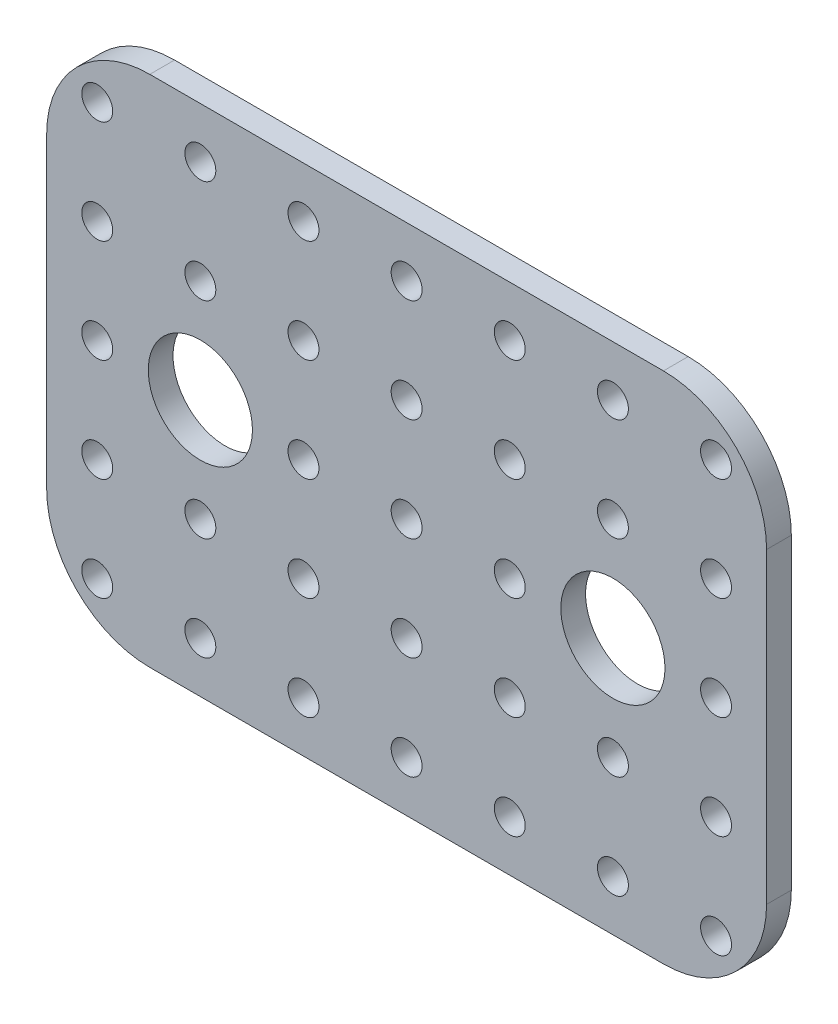
SolidWorks part; units mm, degrees
ref_plane "前视基准面" through (0, 0, 0) normal (0, 0, 1) x (1, 0, 0)
ref_plane "上视基准面" through (0, 0, 0) normal (0, 1, 0) x (1, 0, 0)
ref_plane "右视基准面" through (0, 0, 0) normal (1, 0, 0) x (0, 0, -1)
sketch "草图1" plane through (0, 0, 0) normal (0, 0, 1) x (1, 0, 0)
  line L1 (34.9, -24.9) -> (-34.9, -24.9)
  line L2 (34.9, -24.9) -> (34.9, 24.9)
  line L3 (34.9, 24.9) -> (-34.9, 24.9)
  line L4 (-34.9, -24.9) -> (-34.9, 24.9)
  line L5 (34.9, -24.9) -> (-34.9, 24.9) construction
  line L6 (34.9, 24.9) -> (-34.9, -24.9) construction
  point P0 (0, 0)
  dimension "D1" = 69.8
  dimension "D2" = 49.8
extrude "凸台-拉伸1" add sketch "草图1" along normal blind 2.4
sketch "草图2" plane through (0, 0, 2.4) normal (0, 0, 1) x (1, 0, 0)
  circle A0 centre (30, 20) radius 1.5
  circle A1 centre (20, 20) radius 1.5
  circle A2 centre (10, 20) radius 1.5
  circle A3 centre (0, 20) radius 1.5
  circle A4 centre (-10, 20) radius 1.5
  circle A5 centre (-20, 20) radius 1.5
  circle A6 centre (-30, 20) radius 1.5
  circle A7 centre (20, 10) radius 1.5
  circle A8 centre (10, 10) radius 1.5
  circle A9 centre (0, 10) radius 1.5
  circle A10 centre (-10, 10) radius 1.5
  circle A11 centre (-20, 10) radius 1.5
  circle A12 centre (-30, 10) radius 1.5
  circle A13 centre (20, 0) radius 1.5
  circle A14 centre (10, 0) radius 1.5
  circle A15 centre (0, 0) radius 1.5
  circle A16 centre (-10, 0) radius 1.5
  circle A17 centre (-20, 0) radius 1.5
  circle A18 centre (-30, 0) radius 1.5
  circle A19 centre (20, -10) radius 1.5
  circle A20 centre (10, -10) radius 1.5
  circle A21 centre (0, -10) radius 1.5
  circle A22 centre (-10, -10) radius 1.5
  circle A23 centre (-20, -10) radius 1.5
  circle A24 centre (-30, -10) radius 1.5
  circle A25 centre (20, -20) radius 1.5
  circle A26 centre (10, -20) radius 1.5
  circle A27 centre (0, -20) radius 1.5
  circle A28 centre (-10, -20) radius 1.5
  circle A29 centre (-20, -20) radius 1.5
  circle A30 centre (-30, -20) radius 1.5
  circle A31 centre (30, 10) radius 1.5
  circle A32 centre (30, 0) radius 1.5
  circle A33 centre (30, -10) radius 1.5
  circle A34 centre (30, -20) radius 1.5
  circle A35 centre (-20, 0) radius 5.05
  circle A36 centre (20, 0) radius 5.05
  dimension "D1" = 3
  dimension "D4" = 10.1
  dimension "10.1" = 10.1
  dimension "D2" = 7
  dimension "D3" = 5
extrude "切除-拉伸3" cut sketch "草图2" against normal blind 10
fillet "圆角4" radius 10 1 edges at (34.9, 24.9, 1.2)
fillet "圆角5" radius 10 3 edges at (-34.9, 24.9, 1.2) (-34.9, -24.9, 1.2) (34.9, -24.9, 1.2)
